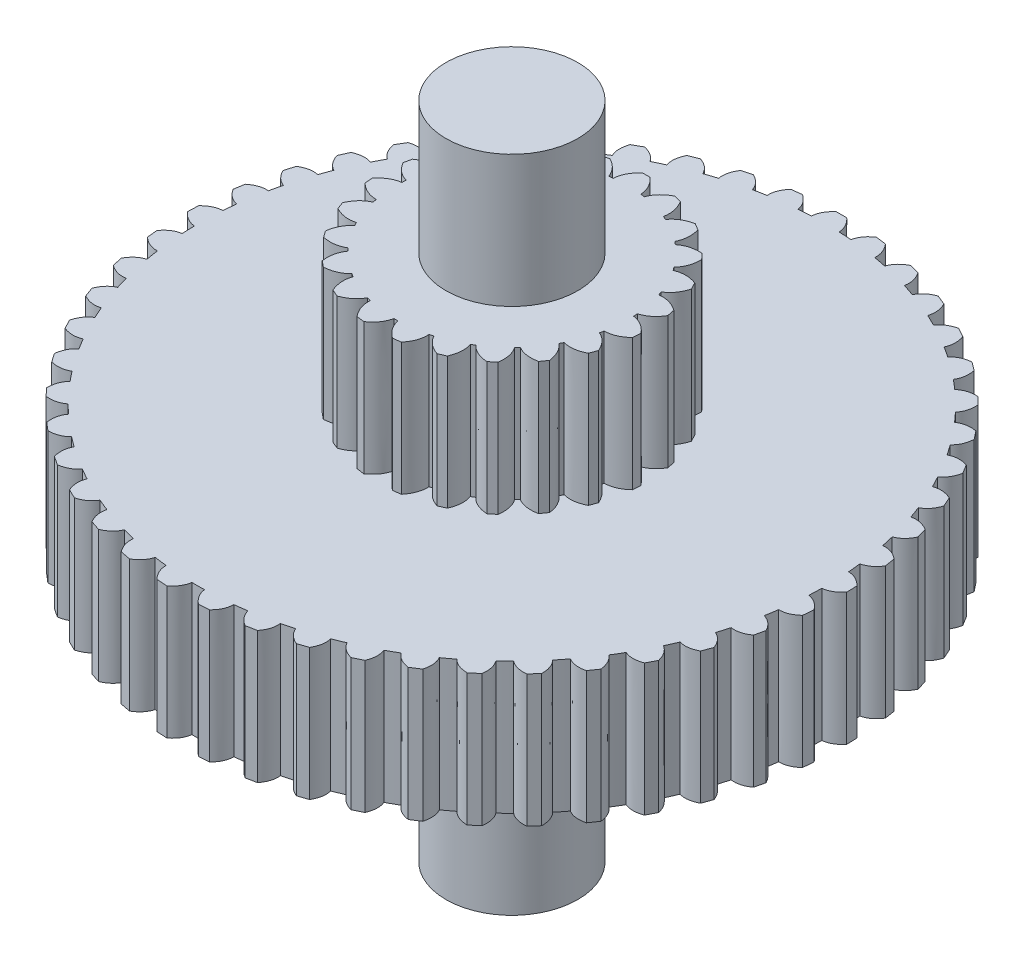
SolidWorks part; units mm, degrees
ref_plane "Front Plane" through (0, 0, 0) normal (0, 0, 1) x (1, 0, 0)
ref_plane "Top Plane" through (0, 0, 0) normal (0, 1, 0) x (1, 0, 0)
ref_plane "Right Plane" through (0, 0, 0) normal (1, 0, 0) x (0, 0, -1)
sketch "Sketch1" plane through (0, 0, 0) normal (0, 1, 0) x (1, 0, 0)
  circle A0 centre (0, 0) radius 2.38
  dimension "D1" = 4.76
extrude "Boss-Extrude1" add sketch "Sketch1" along normal blind 1
sketch "Sketch2" plane through (0, 1, 0) normal (0, 1, 0) x (1, 0, 0)
  line L0 (0, 2.5943) -> (0, 1.7142) construction
  line L1 (0.105, 2.5128) -> (0.105, 2.0785) construction
  line L2 (-0.04, 2.5) -> (0.04, 2.5)
  line L3 (0.28, 2.4846) -> (0.3594, 2.4744)
  line L4 (0.5954, 2.4284) -> (0.6728, 2.4081)
  line L5 (0.9011, 2.3323) -> (0.9752, 2.3023)
  line L6 (1.1919, 2.1979) -> (1.2616, 2.1587)
  line L7 (1.4632, 2.0275) -> (1.5273, 1.9796)
  line L8 (1.7105, 1.8237) -> (1.7679, 1.768)
  line L9 (1.9296, 1.59) -> (1.9795, 1.5275)
  line L10 (2.1171, 1.3302) -> (2.1586, 1.2618)
  line L11 (2.2698, 1.0485) -> (2.3022, 0.9754)
  line L12 (2.3853, 0.7497) -> (2.4081, 0.673)
  line L13 (2.4616, 0.4385) -> (2.4743, 0.3595)
  line L14 (2.4974, 0.1201) -> (2.5, 0.0401)
  line L15 (2.4923, -0.2002) -> (2.4846, -0.2799)
  line L16 (2.4462, -0.5173) -> (2.4284, -0.5953)
  line L17 (2.36, -0.8259) -> (2.3324, -0.901)
  line L18 (2.235, -1.1209) -> (2.198, -1.1918)
  line L19 (2.0733, -1.3975) -> (2.0275, -1.4631)
  line L20 (1.8776, -1.6511) -> (1.8238, -1.7104)
  line L21 (1.651, -1.8777) -> (1.5901, -1.9295)
  line L22 (1.3974, -2.0734) -> (1.3303, -2.117)
  line L23 (1.1207, -2.2351) -> (1.0487, -2.2698)
  line L24 (0.8257, -2.36) -> (0.7498, -2.3852)
  line L25 (0.5172, -2.4463) -> (0.4386, -2.4615)
  line L26 (0.2001, -2.4923) -> (0.1203, -2.4974)
  line L27 (-0.1203, -2.4974) -> (-0.2001, -2.4923)
  line L28 (-0.4386, -2.4615) -> (-0.5172, -2.4463)
  line L29 (-0.7498, -2.3852) -> (-0.8257, -2.36)
  line L30 (-1.0487, -2.2698) -> (-1.1207, -2.2351)
  line L31 (-1.3303, -2.117) -> (-1.3974, -2.0734)
  line L32 (-1.5901, -1.9295) -> (-1.651, -1.8777)
  line L33 (-1.8238, -1.7104) -> (-1.8776, -1.6511)
  line L34 (-2.0275, -1.4631) -> (-2.0733, -1.3975)
  line L35 (-2.198, -1.1918) -> (-2.235, -1.1209)
  line L36 (-2.3324, -0.901) -> (-2.36, -0.8259)
  line L37 (-2.4284, -0.5953) -> (-2.4462, -0.5173)
  line L38 (-2.4846, -0.2799) -> (-2.4923, -0.2002)
  line L39 (-2.5, 0.0401) -> (-2.4974, 0.1201)
  line L40 (-2.4743, 0.3595) -> (-2.4616, 0.4385)
  line L41 (-2.4081, 0.673) -> (-2.3853, 0.7497)
  line L42 (-2.3022, 0.9754) -> (-2.2698, 1.0485)
  line L43 (-2.1586, 1.2618) -> (-2.1171, 1.3302)
  line L44 (-1.9795, 1.5275) -> (-1.9296, 1.59)
  line L45 (-1.7679, 1.768) -> (-1.7105, 1.8237)
  line L46 (-1.5273, 1.9796) -> (-1.4632, 2.0275)
  line L47 (-1.2616, 2.1587) -> (-1.1919, 2.1979)
  line L48 (-0.9752, 2.3023) -> (-0.9011, 2.3323)
  line L49 (-0.6728, 2.4081) -> (-0.5954, 2.4284)
  line L50 (-0.3594, 2.4744) -> (-0.28, 2.4846)
  circle A0 centre (0, 0) radius 2.38 construction
  spline S0 degree 2 poles (0.04, 2.5) (0.1021, 2.4443) (0.105, 2.3743) knots 0 0 0 0.911988 0.911988 0.911988
  spline S1 degree 1 poles (0, 2.38) (0.105, 2.3743) knots 0 0 1 1
  spline S2 degree 1 poles (0, 2.38) (-0.105, 2.3743) knots 0 0 1 1
  spline S3 degree 2 poles (-0.04, 2.5) (-0.1021, 2.4443) (-0.105, 2.3743) knots 0 0 0 0.911988 0.911988 0.911988
  spline S4 degree 2 poles (0.28, 2.4846) (0.2113, 2.4373) (0.1995, 2.3682) knots 0 0 0 0.911988 0.911988 0.911988
  spline S5 degree 1 poles (0.3043, 2.3605) (0.1995, 2.3682) knots 0 0 1 1
  spline S6 degree 1 poles (0.3043, 2.3605) (0.4078, 2.3413) knots 0 0 1 1
  spline S7 degree 2 poles (0.3594, 2.4744) (0.4139, 2.4112) (0.4078, 2.3413) knots 0 0 0 0.911988 0.911988 0.911988
  spline S8 degree 2 poles (0.5954, 2.4284) (0.5212, 2.3903) (0.5007, 2.3232) knots 0 0 0 0.911988 0.911988 0.911988
  spline S9 degree 1 poles (0.6037, 2.3022) (0.5007, 2.3232) knots 0 0 1 1
  spline S10 degree 1 poles (0.6037, 2.3022) (0.7038, 2.27) knots 0 0 1 1
  spline S11 degree 2 poles (0.6728, 2.4081) (0.7188, 2.3385) (0.7038, 2.27) knots 0 0 0 0.911988 0.911988 0.911988
  spline S12 degree 2 poles (0.9011, 2.3323) (0.8226, 2.304) (0.7937, 2.2401) knots 0 0 0 0.911988 0.911988 0.911988
  spline S13 degree 1 poles (0.8931, 2.2061) (0.7937, 2.2401) knots 0 0 1 1
  spline S14 degree 1 poles (0.8931, 2.2061) (0.9883, 2.1613) knots 0 0 1 1
  spline S15 degree 2 poles (0.9752, 2.3023) (1.012, 2.2274) (0.9883, 2.1613) knots 0 0 0 0.911988 0.911988 0.911988
  spline S16 degree 2 poles (1.1919, 2.1979) (1.1105, 2.1799) (1.0736, 2.1203) knots 0 0 0 0.911988 0.911988 0.911988
  spline S17 degree 1 poles (1.1679, 2.0737) (1.0736, 2.1203) knots 0 0 1 1
  spline S18 degree 1 poles (1.1679, 2.0737) (1.2566, 2.0172) knots 0 0 1 1
  spline S19 degree 2 poles (1.2616, 2.1587) (1.2885, 2.0797) (1.2566, 2.0172) knots 0 0 0 0.911988 0.911988 0.911988
  spline S20 degree 2 poles (1.4632, 2.0275) (1.3801, 2.02) (1.3359, 1.9656) knots 0 0 0 0.911988 0.911988 0.911988
  spline S21 degree 1 poles (1.4235, 1.9074) (1.3359, 1.9656) knots 0 0 1 1
  spline S22 degree 1 poles (1.4235, 1.9074) (1.5042, 1.84) knots 0 0 1 1
  spline S23 degree 2 poles (1.5273, 1.9796) (1.5438, 1.8978) (1.5042, 1.84) knots 0 0 0 0.911988 0.911988 0.911988
  spline S24 degree 2 poles (1.7105, 1.8237) (1.6271, 1.8269) (1.5763, 1.7786) knots 0 0 0 0.911988 0.911988 0.911988
  spline S25 degree 1 poles (1.6557, 1.7097) (1.5763, 1.7786) knots 0 0 1 1
  spline S26 degree 1 poles (1.6557, 1.7097) (1.7272, 1.6325) knots 0 0 1 1
  spline S27 degree 2 poles (1.7679, 1.768) (1.7739, 1.6848) (1.7272, 1.6325) knots 0 0 0 0.911988 0.911988 0.911988
  spline S28 degree 2 poles (1.9296, 1.59) (1.8474, 1.6039) (1.7908, 1.5624) knots 0 0 0 0.911988 0.911988 0.911988
  spline S29 degree 1 poles (1.8608, 1.4839) (1.7908, 1.5624) knots 0 0 1 1
  spline S30 degree 1 poles (1.8608, 1.4839) (1.9217, 1.3982) knots 0 0 1 1
  spline S31 degree 2 poles (1.9795, 1.5275) (1.9747, 1.4442) (1.9217, 1.3982) knots 0 0 0 0.911988 0.911988 0.911988
  spline S32 degree 2 poles (2.1171, 1.3302) (2.0373, 1.3545) (1.9759, 1.3206) knots 0 0 0 0.911988 0.911988 0.911988
  spline S33 degree 1 poles (2.0352, 1.2338) (1.9759, 1.3206) knots 0 0 1 1
  spline S34 degree 1 poles (2.0352, 1.2338) (2.0848, 1.141) knots 0 0 1 1
  spline S35 degree 2 poles (2.1586, 1.2618) (2.1432, 1.1798) (2.0848, 1.141) knots 0 0 0 0.911988 0.911988 0.911988
  spline S36 degree 2 poles (2.2698, 1.0485) (2.1938, 1.0828) (2.1285, 1.0571) knots 0 0 0 0.911988 0.911988 0.911988
  spline S37 degree 1 poles (2.1763, 0.9634) (2.1285, 1.0571) knots 0 0 1 1
  spline S38 degree 1 poles (2.1763, 0.9634) (2.2136, 0.865) knots 0 0 1 1
  spline S39 degree 2 poles (2.3022, 0.9754) (2.2765, 0.896) (2.2136, 0.865) knots 0 0 0 0.911988 0.911988 0.911988
  spline S40 degree 2 poles (2.3853, 0.7497) (2.3142, 0.7934) (2.2462, 0.7762) knots 0 0 0 0.911988 0.911988 0.911988
  spline S41 degree 1 poles (2.2816, 0.6772) (2.2462, 0.7762) knots 0 0 1 1
  spline S42 degree 1 poles (2.2816, 0.6772) (2.306, 0.5749) knots 0 0 1 1
  spline S43 degree 2 poles (2.4081, 0.673) (2.3724, 0.5976) (2.306, 0.5749) knots 0 0 0 0.911988 0.911988 0.911988
  spline S44 degree 2 poles (2.4616, 0.4385) (2.3967, 0.4909) (2.3271, 0.4826) knots 0 0 0 0.911988 0.911988 0.911988
  spline S45 degree 1 poles (2.3495, 0.3798) (2.3271, 0.4826) knots 0 0 1 1
  spline S46 degree 1 poles (2.3495, 0.3798) (2.3606, 0.2753) knots 0 0 1 1
  spline S47 degree 2 poles (2.4743, 0.3595) (2.4293, 0.2893) (2.3606, 0.2753) knots 0 0 0 0.911988 0.911988 0.911988
  spline S48 degree 2 poles (2.4974, 0.1201) (2.4398, 0.1804) (2.3697, 0.181) knots 0 0 0 0.911988 0.911988 0.911988
  spline S49 degree 1 poles (2.3788, 0.0763) (2.3697, 0.181) knots 0 0 1 1
  spline S50 degree 1 poles (2.3788, 0.0763) (2.3764, -0.0288) knots 0 0 1 1
  spline S51 degree 2 poles (2.5, 0.0401) (2.4464, -0.0237) (2.3764, -0.0288) knots 0 0 0 0.911988 0.911988 0.911988
  spline S52 degree 2 poles (2.4923, -0.2002) (2.4428, -0.133) (2.3734, -0.1235) knots 0 0 0 0.911988 0.911988 0.911988
  spline S53 degree 1 poles (2.369, -0.2285) (2.3734, -0.1235) knots 0 0 1 1
  spline S54 degree 1 poles (2.369, -0.2285) (2.3532, -0.3325) knots 0 0 1 1
  spline S55 degree 2 poles (2.4846, -0.2799) (2.4232, -0.3364) (2.3532, -0.3325) knots 0 0 0 0.911988 0.911988 0.911988
  spline S56 degree 2 poles (2.4462, -0.5173) (2.4058, -0.4443) (2.3381, -0.426) knots 0 0 0 0.911988 0.911988 0.911988
  spline S57 degree 1 poles (2.3203, -0.5296) (2.3381, -0.426) knots 0 0 1 1
  spline S58 degree 1 poles (2.3203, -0.5296) (2.2914, -0.6307) knots 0 0 1 1
  spline S59 degree 2 poles (2.4284, -0.5953) (2.3603, -0.6435) (2.2914, -0.6307) knots 0 0 0 0.911988 0.911988 0.911988
  spline S60 degree 2 poles (2.36, -0.8259) (2.3292, -0.7483) (2.2644, -0.7214) knots 0 0 0 0.911988 0.911988 0.911988
  spline S61 degree 1 poles (2.2336, -0.822) (2.2644, -0.7214) knots 0 0 1 1
  spline S62 degree 1 poles (2.2336, -0.822) (2.1919, -0.9185) knots 0 0 1 1
  spline S63 degree 2 poles (2.3324, -0.901) (2.2587, -0.94) (2.1919, -0.9185) knots 0 0 0 0.911988 0.911988 0.911988
  spline S64 degree 2 poles (2.235, -1.1209) (2.2144, -1.04) (2.1536, -1.0051) knots 0 0 0 0.911988 0.911988 0.911988
  spline S65 degree 1 poles (2.1101, -1.1008) (2.1536, -1.0051) knots 0 0 1 1
  spline S66 degree 1 poles (2.1101, -1.1008) (2.0564, -1.1913) knots 0 0 1 1
  spline S67 degree 2 poles (2.198, -1.1918) (2.1199, -1.2212) (2.0564, -1.1913) knots 0 0 0 0.911988 0.911988 0.911988
  spline S68 degree 2 poles (2.0733, -1.3975) (2.0632, -1.3147) (2.0074, -1.2722) knots 0 0 0 0.911988 0.911988 0.911988
  spline S69 degree 1 poles (1.952, -1.3616) (2.0074, -1.2722) knots 0 0 1 1
  spline S70 degree 1 poles (1.952, -1.3616) (1.8872, -1.4445) knots 0 0 1 1
  spline S71 degree 2 poles (2.0275, -1.4631) (1.9463, -1.4822) (1.8872, -1.4445) knots 0 0 0 0.911988 0.911988 0.911988
  spline S72 degree 2 poles (1.8776, -1.6511) (1.8782, -1.5677) (1.8282, -1.5185) knots 0 0 0 0.911988 0.911988 0.911988
  spline S73 degree 1 poles (1.7619, -1.6001) (1.8282, -1.5185) knots 0 0 1 1
  spline S74 degree 1 poles (1.7619, -1.6001) (1.687, -1.6739) knots 0 0 1 1
  spline S75 degree 2 poles (1.8238, -1.7104) (1.7408, -1.7189) (1.687, -1.6739) knots 0 0 0 0.911988 0.911988 0.911988
  spline S76 degree 2 poles (1.651, -1.8777) (1.6623, -1.795) (1.619, -1.7398) knots 0 0 0 0.911988 0.911988 0.911988
  spline S77 degree 1 poles (1.5428, -1.8122) (1.619, -1.7398) knots 0 0 1 1
  spline S78 degree 1 poles (1.5428, -1.8122) (1.4591, -1.8759) knots 0 0 1 1
  spline S79 degree 2 poles (1.5901, -1.9295) (1.5067, -1.9274) (1.4591, -1.8759) knots 0 0 0 0.911988 0.911988 0.911988
  spline S80 degree 2 poles (1.3974, -2.0734) (1.4191, -1.9928) (1.3832, -1.9326) knots 0 0 0 0.911988 0.911988 0.911988
  spline S81 degree 1 poles (1.2984, -1.9946) (1.3832, -1.9326) knots 0 0 1 1
  spline S82 degree 1 poles (1.2984, -1.9946) (1.2072, -2.0471) knots 0 0 1 1
  spline S83 degree 2 poles (1.3303, -2.117) (1.2479, -2.1043) (1.2072, -2.0471) knots 0 0 0 0.911988 0.911988 0.911988
  spline S84 degree 2 poles (1.1207, -2.2351) (1.1526, -2.158) (1.1248, -2.0936) knots 0 0 0 0.911988 0.911988 0.911988
  spline S85 degree 1 poles (1.0326, -2.1443) (1.1248, -2.0936) knots 0 0 1 1
  spline S86 degree 1 poles (1.0326, -2.1443) (0.9355, -2.1847) knots 0 0 1 1
  spline S87 degree 2 poles (1.0487, -2.2698) (0.9685, -2.2466) (0.9355, -2.1847) knots 0 0 0 0.911988 0.911988 0.911988
  spline S88 degree 2 poles (0.8257, -2.36) (0.8672, -2.2876) (0.8478, -2.2202) knots 0 0 0 0.911988 0.911988 0.911988
  spline S89 degree 1 poles (0.75, -2.2588) (0.8478, -2.2202) knots 0 0 1 1
  spline S90 degree 1 poles (0.75, -2.2588) (0.6485, -2.2864) knots 0 0 1 1
  spline S91 degree 2 poles (0.7498, -2.3852) (0.6733, -2.352) (0.6485, -2.2864) knots 0 0 0 0.911988 0.911988 0.911988
  spline S92 degree 2 poles (0.5172, -2.4463) (0.5675, -2.3797) (0.5569, -2.3104) knots 0 0 0 0.911988 0.911988 0.911988
  spline S93 degree 1 poles (0.455, -2.3361) (0.5569, -2.3104) knots 0 0 1 1
  spline S94 degree 1 poles (0.455, -2.3361) (0.3508, -2.3505) knots 0 0 1 1
  spline S95 degree 2 poles (0.4386, -2.4615) (0.367, -2.4188) (0.3508, -2.3505) knots 0 0 0 0.911988 0.911988 0.911988
  spline S96 degree 2 poles (0.2001, -2.4923) (0.2585, -2.4328) (0.2569, -2.3626) knots 0 0 0 0.911988 0.911988 0.911988
  spline S97 degree 1 poles (0.1525, -2.3751) (0.2569, -2.3626) knots 0 0 1 1
  spline S98 degree 1 poles (0.1525, -2.3751) (0.0473, -2.3761) knots 0 0 1 1
  spline S99 degree 2 poles (0.1203, -2.4974) (0.0547, -2.4459) (0.0473, -2.3761) knots 0 0 0 0.911988 0.911988 0.911988
  spline S100 degree 2 poles (-0.1203, -2.4974) (-0.0547, -2.4459) (-0.0473, -2.3761) knots 0 0 0 0.911988 0.911988 0.911988
  spline S101 degree 1 poles (-0.1525, -2.3751) (-0.0473, -2.3761) knots 0 0 1 1
  spline S102 degree 1 poles (-0.1525, -2.3751) (-0.2569, -2.3626) knots 0 0 1 1
  spline S103 degree 2 poles (-0.2001, -2.4923) (-0.2585, -2.4328) (-0.2569, -2.3626) knots 0 0 0 0.911988 0.911988 0.911988
  spline S104 degree 2 poles (-0.4386, -2.4615) (-0.367, -2.4188) (-0.3508, -2.3505) knots 0 0 0 0.911988 0.911988 0.911988
  spline S105 degree 1 poles (-0.455, -2.3361) (-0.3508, -2.3505) knots 0 0 1 1
  spline S106 degree 1 poles (-0.455, -2.3361) (-0.5569, -2.3104) knots 0 0 1 1
  spline S107 degree 2 poles (-0.5172, -2.4463) (-0.5675, -2.3797) (-0.5569, -2.3104) knots 0 0 0 0.911988 0.911988 0.911988
  spline S108 degree 2 poles (-0.7498, -2.3852) (-0.6733, -2.352) (-0.6485, -2.2864) knots 0 0 0 0.911988 0.911988 0.911988
  spline S109 degree 1 poles (-0.75, -2.2588) (-0.6485, -2.2864) knots 0 0 1 1
  spline S110 degree 1 poles (-0.75, -2.2588) (-0.8478, -2.2202) knots 0 0 1 1
  spline S111 degree 2 poles (-0.8257, -2.36) (-0.8672, -2.2876) (-0.8478, -2.2202) knots 0 0 0 0.911988 0.911988 0.911988
  spline S112 degree 2 poles (-1.0487, -2.2698) (-0.9685, -2.2466) (-0.9355, -2.1847) knots 0 0 0 0.911988 0.911988 0.911988
  spline S113 degree 1 poles (-1.0326, -2.1443) (-0.9355, -2.1847) knots 0 0 1 1
  spline S114 degree 1 poles (-1.0326, -2.1443) (-1.1248, -2.0936) knots 0 0 1 1
  spline S115 degree 2 poles (-1.1207, -2.2351) (-1.1526, -2.158) (-1.1248, -2.0936) knots 0 0 0 0.911988 0.911988 0.911988
  spline S116 degree 2 poles (-1.3303, -2.117) (-1.2479, -2.1043) (-1.2072, -2.0471) knots 0 0 0 0.911988 0.911988 0.911988
  spline S117 degree 1 poles (-1.2984, -1.9946) (-1.2072, -2.0471) knots 0 0 1 1
  spline S118 degree 1 poles (-1.2984, -1.9946) (-1.3832, -1.9326) knots 0 0 1 1
  spline S119 degree 2 poles (-1.3974, -2.0734) (-1.4191, -1.9928) (-1.3832, -1.9326) knots 0 0 0 0.911988 0.911988 0.911988
  spline S120 degree 2 poles (-1.5901, -1.9295) (-1.5067, -1.9274) (-1.4591, -1.8759) knots 0 0 0 0.911988 0.911988 0.911988
  spline S121 degree 1 poles (-1.5428, -1.8122) (-1.4591, -1.8759) knots 0 0 1 1
  spline S122 degree 1 poles (-1.5428, -1.8122) (-1.619, -1.7398) knots 0 0 1 1
  spline S123 degree 2 poles (-1.651, -1.8777) (-1.6623, -1.795) (-1.619, -1.7398) knots 0 0 0 0.911988 0.911988 0.911988
  spline S124 degree 2 poles (-1.8238, -1.7104) (-1.7408, -1.7189) (-1.687, -1.6739) knots 0 0 0 0.911988 0.911988 0.911988
  spline S125 degree 1 poles (-1.7619, -1.6001) (-1.687, -1.6739) knots 0 0 1 1
  spline S126 degree 1 poles (-1.7619, -1.6001) (-1.8282, -1.5185) knots 0 0 1 1
  spline S127 degree 2 poles (-1.8776, -1.6511) (-1.8782, -1.5677) (-1.8282, -1.5185) knots 0 0 0 0.911988 0.911988 0.911988
  spline S128 degree 2 poles (-2.0275, -1.4631) (-1.9463, -1.4822) (-1.8872, -1.4445) knots 0 0 0 0.911988 0.911988 0.911988
  spline S129 degree 1 poles (-1.952, -1.3616) (-1.8872, -1.4445) knots 0 0 1 1
  spline S130 degree 1 poles (-1.952, -1.3616) (-2.0074, -1.2722) knots 0 0 1 1
  spline S131 degree 2 poles (-2.0733, -1.3975) (-2.0632, -1.3147) (-2.0074, -1.2722) knots 0 0 0 0.911988 0.911988 0.911988
  spline S132 degree 2 poles (-2.198, -1.1918) (-2.1199, -1.2212) (-2.0564, -1.1913) knots 0 0 0 0.911988 0.911988 0.911988
  spline S133 degree 1 poles (-2.1101, -1.1008) (-2.0564, -1.1913) knots 0 0 1 1
  spline S134 degree 1 poles (-2.1101, -1.1008) (-2.1536, -1.0051) knots 0 0 1 1
  spline S135 degree 2 poles (-2.235, -1.1209) (-2.2144, -1.04) (-2.1536, -1.0051) knots 0 0 0 0.911988 0.911988 0.911988
  spline S136 degree 2 poles (-2.3324, -0.901) (-2.2587, -0.94) (-2.1919, -0.9185) knots 0 0 0 0.911988 0.911988 0.911988
  spline S137 degree 1 poles (-2.2336, -0.822) (-2.1919, -0.9185) knots 0 0 1 1
  spline S138 degree 1 poles (-2.2336, -0.822) (-2.2644, -0.7214) knots 0 0 1 1
  spline S139 degree 2 poles (-2.36, -0.8259) (-2.3292, -0.7483) (-2.2644, -0.7214) knots 0 0 0 0.911988 0.911988 0.911988
  spline S140 degree 2 poles (-2.4284, -0.5953) (-2.3603, -0.6435) (-2.2914, -0.6307) knots 0 0 0 0.911988 0.911988 0.911988
  spline S141 degree 1 poles (-2.3203, -0.5296) (-2.2914, -0.6307) knots 0 0 1 1
  spline S142 degree 1 poles (-2.3203, -0.5296) (-2.3381, -0.426) knots 0 0 1 1
  spline S143 degree 2 poles (-2.4462, -0.5173) (-2.4058, -0.4443) (-2.3381, -0.426) knots 0 0 0 0.911988 0.911988 0.911988
  spline S144 degree 2 poles (-2.4846, -0.2799) (-2.4232, -0.3364) (-2.3532, -0.3325) knots 0 0 0 0.911988 0.911988 0.911988
  spline S145 degree 1 poles (-2.369, -0.2285) (-2.3532, -0.3325) knots 0 0 1 1
  spline S146 degree 1 poles (-2.369, -0.2285) (-2.3734, -0.1235) knots 0 0 1 1
  spline S147 degree 2 poles (-2.4923, -0.2002) (-2.4428, -0.133) (-2.3734, -0.1235) knots 0 0 0 0.911988 0.911988 0.911988
  spline S148 degree 2 poles (-2.5, 0.0401) (-2.4464, -0.0237) (-2.3764, -0.0288) knots 0 0 0 0.911988 0.911988 0.911988
  spline S149 degree 1 poles (-2.3788, 0.0763) (-2.3764, -0.0288) knots 0 0 1 1
  spline S150 degree 1 poles (-2.3788, 0.0763) (-2.3697, 0.181) knots 0 0 1 1
  spline S151 degree 2 poles (-2.4974, 0.1201) (-2.4398, 0.1804) (-2.3697, 0.181) knots 0 0 0 0.911988 0.911988 0.911988
  spline S152 degree 2 poles (-2.4743, 0.3595) (-2.4293, 0.2893) (-2.3606, 0.2753) knots 0 0 0 0.911988 0.911988 0.911988
  spline S153 degree 1 poles (-2.3495, 0.3798) (-2.3606, 0.2753) knots 0 0 1 1
  spline S154 degree 1 poles (-2.3495, 0.3798) (-2.3271, 0.4826) knots 0 0 1 1
  spline S155 degree 2 poles (-2.4616, 0.4385) (-2.3967, 0.4909) (-2.3271, 0.4826) knots 0 0 0 0.911988 0.911988 0.911988
  spline S156 degree 2 poles (-2.4081, 0.673) (-2.3724, 0.5976) (-2.306, 0.5749) knots 0 0 0 0.911988 0.911988 0.911988
  spline S157 degree 1 poles (-2.2816, 0.6772) (-2.306, 0.5749) knots 0 0 1 1
  spline S158 degree 1 poles (-2.2816, 0.6772) (-2.2462, 0.7762) knots 0 0 1 1
  spline S159 degree 2 poles (-2.3853, 0.7497) (-2.3142, 0.7934) (-2.2462, 0.7762) knots 0 0 0 0.911988 0.911988 0.911988
  spline S160 degree 2 poles (-2.3022, 0.9754) (-2.2765, 0.896) (-2.2136, 0.865) knots 0 0 0 0.911988 0.911988 0.911988
  spline S161 degree 1 poles (-2.1763, 0.9634) (-2.2136, 0.865) knots 0 0 1 1
  spline S162 degree 1 poles (-2.1763, 0.9634) (-2.1285, 1.0571) knots 0 0 1 1
  spline S163 degree 2 poles (-2.2698, 1.0485) (-2.1938, 1.0828) (-2.1285, 1.0571) knots 0 0 0 0.911988 0.911988 0.911988
  spline S164 degree 2 poles (-2.1586, 1.2618) (-2.1432, 1.1798) (-2.0848, 1.141) knots 0 0 0 0.911988 0.911988 0.911988
  spline S165 degree 1 poles (-2.0352, 1.2338) (-2.0848, 1.141) knots 0 0 1 1
  spline S166 degree 1 poles (-2.0352, 1.2338) (-1.9759, 1.3206) knots 0 0 1 1
  spline S167 degree 2 poles (-2.1171, 1.3302) (-2.0373, 1.3545) (-1.9759, 1.3206) knots 0 0 0 0.911988 0.911988 0.911988
  spline S168 degree 2 poles (-1.9795, 1.5275) (-1.9747, 1.4442) (-1.9217, 1.3982) knots 0 0 0 0.911988 0.911988 0.911988
  spline S169 degree 1 poles (-1.8608, 1.4839) (-1.9217, 1.3982) knots 0 0 1 1
  spline S170 degree 1 poles (-1.8608, 1.4839) (-1.7908, 1.5624) knots 0 0 1 1
  spline S171 degree 2 poles (-1.9296, 1.59) (-1.8474, 1.6039) (-1.7908, 1.5624) knots 0 0 0 0.911988 0.911988 0.911988
  spline S172 degree 2 poles (-1.7679, 1.768) (-1.7739, 1.6848) (-1.7272, 1.6325) knots 0 0 0 0.911988 0.911988 0.911988
  spline S173 degree 1 poles (-1.6557, 1.7097) (-1.7272, 1.6325) knots 0 0 1 1
  spline S174 degree 1 poles (-1.6557, 1.7097) (-1.5763, 1.7786) knots 0 0 1 1
  spline S175 degree 2 poles (-1.7105, 1.8237) (-1.6271, 1.8269) (-1.5763, 1.7786) knots 0 0 0 0.911988 0.911988 0.911988
  spline S176 degree 2 poles (-1.5273, 1.9796) (-1.5438, 1.8978) (-1.5042, 1.84) knots 0 0 0 0.911988 0.911988 0.911988
  spline S177 degree 1 poles (-1.4235, 1.9074) (-1.5042, 1.84) knots 0 0 1 1
  spline S178 degree 1 poles (-1.4235, 1.9074) (-1.3359, 1.9656) knots 0 0 1 1
  spline S179 degree 2 poles (-1.4632, 2.0275) (-1.3801, 2.02) (-1.3359, 1.9656) knots 0 0 0 0.911988 0.911988 0.911988
  spline S180 degree 2 poles (-1.2616, 2.1587) (-1.2885, 2.0797) (-1.2566, 2.0172) knots 0 0 0 0.911988 0.911988 0.911988
  spline S181 degree 1 poles (-1.1679, 2.0737) (-1.2566, 2.0172) knots 0 0 1 1
  spline S182 degree 1 poles (-1.1679, 2.0737) (-1.0736, 2.1203) knots 0 0 1 1
  spline S183 degree 2 poles (-1.1919, 2.1979) (-1.1105, 2.1799) (-1.0736, 2.1203) knots 0 0 0 0.911988 0.911988 0.911988
  spline S184 degree 2 poles (-0.9752, 2.3023) (-1.012, 2.2274) (-0.9883, 2.1613) knots 0 0 0 0.911988 0.911988 0.911988
  spline S185 degree 1 poles (-0.8931, 2.2061) (-0.9883, 2.1613) knots 0 0 1 1
  spline S186 degree 1 poles (-0.8931, 2.2061) (-0.7937, 2.2401) knots 0 0 1 1
  spline S187 degree 2 poles (-0.9011, 2.3323) (-0.8226, 2.304) (-0.7937, 2.2401) knots 0 0 0 0.911988 0.911988 0.911988
  spline S188 degree 2 poles (-0.6728, 2.4081) (-0.7188, 2.3385) (-0.7038, 2.27) knots 0 0 0 0.911988 0.911988 0.911988
  spline S189 degree 1 poles (-0.6037, 2.3022) (-0.7038, 2.27) knots 0 0 1 1
  spline S190 degree 1 poles (-0.6037, 2.3022) (-0.5007, 2.3232) knots 0 0 1 1
  spline S191 degree 2 poles (-0.5954, 2.4284) (-0.5212, 2.3903) (-0.5007, 2.3232) knots 0 0 0 0.911988 0.911988 0.911988
  spline S192 degree 2 poles (-0.3594, 2.4744) (-0.4139, 2.4112) (-0.4078, 2.3413) knots 0 0 0 0.911988 0.911988 0.911988
  spline S193 degree 1 poles (-0.3043, 2.3605) (-0.4078, 2.3413) knots 0 0 1 1
  spline S194 degree 1 poles (-0.3043, 2.3605) (-0.1995, 2.3682) knots 0 0 1 1
  spline S195 degree 2 poles (-0.28, 2.4846) (-0.2113, 2.4373) (-0.1995, 2.3682) knots 0 0 0 0.911988 0.911988 0.911988
  point P13 (0, 2.5)
  dimension "D1" = 0.105
  dimension "D2" = 0.04
  dimension "D3" = 2.5
extrude "Boss-Extrude2" add sketch "Sketch2" against normal blind 1
sketch "Sketch3" plane through (0, 1, 0) normal (0, 1, 0) x (1, 0, 0)
  circle A0 centre (0, 0) radius 0.88
  dimension "D1" = 1.76
extrude "Boss-Extrude3" add sketch "Sketch3" along normal blind 1
sketch "Sketch4" plane through (0, 2, 0) normal (0, 1, 0) x (1, 0, 0)
  line L0 (0, 1.0523) -> (0, 0.6388) construction
  line L1 (0.105, 0.9663) -> (0.105, 0.705) construction
  line L2 (-0.03, 1.0197) -> (0.03, 1.0197)
  line L3 (0.2462, 0.9899) -> (0.304, 0.9738)
  line L4 (0.5042, 0.8868) -> (0.5554, 0.8556)
  line L5 (0.7247, 0.7179) -> (0.7657, 0.674)
  line L6 (0.8915, 0.4957) -> (0.9191, 0.4425)
  line L7 (0.9922, 0.2368) -> (1.0044, 0.1781)
  line L8 (1.0193, -0.0397) -> (1.0152, -0.0995)
  line L9 (0.9708, -0.3132) -> (0.9507, -0.3697)
  line L10 (0.8503, -0.5635) -> (0.8157, -0.6125)
  line L11 (0.6668, -0.772) -> (0.6202, -0.8099)
  line L12 (0.4338, -0.9233) -> (0.3787, -0.9472)
  line L13 (0.1686, -1.0061) -> (0.1091, -1.0143)
  line L14 (-0.1091, -1.0143) -> (-0.1686, -1.0061)
  line L15 (-0.3787, -0.9472) -> (-0.4338, -0.9233)
  line L16 (-0.6202, -0.8099) -> (-0.6668, -0.772)
  line L17 (-0.8157, -0.6125) -> (-0.8503, -0.5635)
  line L18 (-0.9507, -0.3697) -> (-0.9708, -0.3132)
  line L19 (-1.0152, -0.0995) -> (-1.0193, -0.0397)
  line L20 (-1.0044, 0.1781) -> (-0.9922, 0.2368)
  line L21 (-0.9191, 0.4425) -> (-0.8915, 0.4957)
  line L22 (-0.7657, 0.674) -> (-0.7247, 0.7179)
  line L23 (-0.5554, 0.8556) -> (-0.5042, 0.8868)
  line L24 (-0.304, 0.9738) -> (-0.2462, 0.9899)
  circle A0 centre (0, 0) radius 0.88 construction
  spline S0 degree 2 poles (0.03, 1.0197) (0.1014, 0.9525) (0.105, 0.8694) knots 0 0 0 0.904085 0.904085 0.904085
  spline S1 degree 1 poles (0, 0.88) (0.105, 0.8694) knots 0 0 1 1
  spline S2 degree 1 poles (0, 0.88) (-0.105, 0.8694) knots 0 0 1 1
  spline S3 degree 2 poles (-0.03, 1.0197) (-0.1014, 0.9525) (-0.105, 0.8694) knots 0 0 0 0.904085 0.904085 0.904085
  spline S4 degree 2 poles (0.2462, 0.9899) (0.1593, 0.9446) (0.1335, 0.8655) knots 0 0 0 0.904085 0.904085 0.904085
  spline S5 degree 2 poles (0.304, 0.9738) (0.3546, 0.8898) (0.3357, 0.8088) knots 0 0 0 0.904085 0.904085 0.904085
  spline S6 degree 1 poles (0.2374, 0.8474) (0.3357, 0.8088) knots 0 0 1 1
  spline S7 degree 1 poles (0.2374, 0.8474) (0.1335, 0.8655) knots 0 0 1 1
  spline S8 degree 2 poles (0.5042, 0.8868) (0.4083, 0.8665) (0.362, 0.7974) knots 0 0 0 0.904085 0.904085 0.904085
  spline S9 degree 2 poles (0.5554, 0.8556) (0.5816, 0.7612) (0.5414, 0.6883) knots 0 0 0 0.904085 0.904085 0.904085
  spline S10 degree 1 poles (0.4572, 0.7519) (0.5414, 0.6883) knots 0 0 1 1
  spline S11 degree 1 poles (0.4572, 0.7519) (0.362, 0.7974) knots 0 0 1 1
  spline S12 degree 2 poles (0.7247, 0.7179) (0.6269, 0.7243) (0.5637, 0.6701) knots 0 0 0 0.904085 0.904085 0.904085
  spline S13 degree 2 poles (0.7657, 0.674) (0.7653, 0.576) (0.707, 0.5167) knots 0 0 0 0.904085 0.904085 0.904085
  spline S14 degree 1 poles (0.6431, 0.6006) (0.707, 0.5167) knots 0 0 1 1
  spline S15 degree 1 poles (0.6431, 0.6006) (0.5637, 0.6701) knots 0 0 1 1
  spline S16 degree 2 poles (0.8915, 0.4957) (0.7991, 0.5283) (0.7236, 0.4932) knots 0 0 0 0.904085 0.904085 0.904085
  spline S17 degree 2 poles (0.9191, 0.4425) (0.8924, 0.3482) (0.8202, 0.3067) knots 0 0 0 0.904085 0.904085 0.904085
  spline S18 degree 1 poles (0.7813, 0.4049) (0.8202, 0.3067) knots 0 0 1 1
  spline S19 degree 1 poles (0.7813, 0.4049) (0.7236, 0.4932) knots 0 0 1 1
  spline S20 degree 2 poles (0.9922, 0.2368) (0.912, 0.2931) (0.8298, 0.2797) knots 0 0 0 0.904085 0.904085 0.904085
  spline S21 degree 2 poles (1.0044, 0.1781) (0.9532, 0.0945) (0.8726, 0.0741) knots 0 0 0 0.904085 0.904085 0.904085
  spline S22 degree 1 poles (0.8616, 0.179) (0.8726, 0.0741) knots 0 0 1 1
  spline S23 degree 1 poles (0.8616, 0.179) (0.8298, 0.2797) knots 0 0 1 1
  spline S24 degree 2 poles (1.0193, -0.0397) (0.9572, 0.0362) (0.8745, 0.0454) knots 0 0 0 0.904085 0.904085 0.904085
  spline S25 degree 2 poles (1.0152, -0.0995) (0.9434, -0.1662) (0.8602, -0.1641) knots 0 0 0 0.904085 0.904085 0.904085
  spline S26 degree 1 poles (0.8779, -0.0601) (0.8602, -0.1641) knots 0 0 1 1
  spline S27 degree 1 poles (0.8779, -0.0601) (0.8745, 0.0454) knots 0 0 1 1
  spline S28 degree 2 poles (0.9708, -0.3132) (0.9315, -0.2234) (0.8544, -0.1922) knots 0 0 0 0.904085 0.904085 0.904085
  spline S29 degree 2 poles (0.9507, -0.3697) (0.8636, -0.4145) (0.784, -0.3901) knots 0 0 0 0.904085 0.904085 0.904085
  spline S30 degree 1 poles (0.8292, -0.2947) (0.784, -0.3901) knots 0 0 1 1
  spline S31 degree 1 poles (0.8292, -0.2947) (0.8544, -0.1922) knots 0 0 1 1
  spline S32 degree 2 poles (0.8503, -0.5635) (0.8367, -0.4665) (0.7708, -0.4156) knots 0 0 0 0.904085 0.904085 0.904085
  spline S33 degree 2 poles (0.8157, -0.6125) (0.7197, -0.6321) (0.6497, -0.5871) knots 0 0 0 0.904085 0.904085 0.904085
  spline S34 degree 1 poles (0.7189, -0.5075) (0.6497, -0.5871) knots 0 0 1 1
  spline S35 degree 1 poles (0.7189, -0.5075) (0.7708, -0.4156) knots 0 0 1 1
  spline S36 degree 2 poles (0.6668, -0.772) (0.6798, -0.6749) (0.6301, -0.6081) knots 0 0 0 0.904085 0.904085 0.904085
  spline S37 degree 2 poles (0.6202, -0.8099) (0.5225, -0.8029) (0.4672, -0.7407) knots 0 0 0 0.904085 0.904085 0.904085
  spline S38 degree 1 poles (0.5554, -0.6826) (0.4672, -0.7407) knots 0 0 1 1
  spline S39 degree 1 poles (0.5554, -0.6826) (0.6301, -0.6081) knots 0 0 1 1
  spline S40 degree 2 poles (0.4338, -0.9233) (0.4725, -0.8333) (0.4427, -0.7556) knots 0 0 0 0.904085 0.904085 0.904085
  spline S41 degree 2 poles (0.3787, -0.9472) (0.2865, -0.9141) (0.2501, -0.8392) knots 0 0 0 0.904085 0.904085 0.904085
  spline S42 degree 1 poles (0.3506, -0.8071) (0.2501, -0.8392) knots 0 0 1 1
  spline S43 degree 1 poles (0.3506, -0.8071) (0.4427, -0.7556) knots 0 0 1 1
  spline S44 degree 2 poles (0.1686, -1.0061) (0.2302, -0.9298) (0.2224, -0.847) knots 0 0 0 0.904085 0.904085 0.904085
  spline S45 degree 2 poles (0.1091, -1.0143) (0.0292, -0.9575) (0.0144, -0.8756) knots 0 0 0 0.904085 0.904085 0.904085
  spline S46 degree 1 poles (0.1198, -0.8718) (0.0144, -0.8756) knots 0 0 1 1
  spline S47 degree 1 poles (0.1198, -0.8718) (0.2224, -0.847) knots 0 0 1 1
  spline S48 degree 2 poles (-0.1091, -1.0143) (-0.0292, -0.9575) (-0.0144, -0.8756) knots 0 0 0 0.904085 0.904085 0.904085
  spline S49 degree 2 poles (-0.1686, -1.0061) (-0.2302, -0.9298) (-0.2224, -0.847) knots 0 0 0 0.904085 0.904085 0.904085
  spline S50 degree 1 poles (-0.1198, -0.8718) (-0.2224, -0.847) knots 0 0 1 1
  spline S51 degree 1 poles (-0.1198, -0.8718) (-0.0144, -0.8756) knots 0 0 1 1
  spline S52 degree 2 poles (-0.3787, -0.9472) (-0.2865, -0.9141) (-0.2501, -0.8392) knots 0 0 0 0.904085 0.904085 0.904085
  spline S53 degree 2 poles (-0.4338, -0.9233) (-0.4725, -0.8333) (-0.4427, -0.7556) knots 0 0 0 0.904085 0.904085 0.904085
  spline S54 degree 1 poles (-0.3506, -0.8071) (-0.4427, -0.7556) knots 0 0 1 1
  spline S55 degree 1 poles (-0.3506, -0.8071) (-0.2501, -0.8392) knots 0 0 1 1
  spline S56 degree 2 poles (-0.6202, -0.8099) (-0.5225, -0.8029) (-0.4672, -0.7407) knots 0 0 0 0.904085 0.904085 0.904085
  spline S57 degree 2 poles (-0.6668, -0.772) (-0.6798, -0.6749) (-0.6301, -0.6081) knots 0 0 0 0.904085 0.904085 0.904085
  spline S58 degree 1 poles (-0.5554, -0.6826) (-0.6301, -0.6081) knots 0 0 1 1
  spline S59 degree 1 poles (-0.5554, -0.6826) (-0.4672, -0.7407) knots 0 0 1 1
  spline S60 degree 2 poles (-0.8157, -0.6125) (-0.7197, -0.6321) (-0.6497, -0.5871) knots 0 0 0 0.904085 0.904085 0.904085
  spline S61 degree 2 poles (-0.8503, -0.5635) (-0.8367, -0.4665) (-0.7708, -0.4156) knots 0 0 0 0.904085 0.904085 0.904085
  spline S62 degree 1 poles (-0.7189, -0.5075) (-0.7708, -0.4156) knots 0 0 1 1
  spline S63 degree 1 poles (-0.7189, -0.5075) (-0.6497, -0.5871) knots 0 0 1 1
  spline S64 degree 2 poles (-0.9507, -0.3697) (-0.8636, -0.4145) (-0.784, -0.3901) knots 0 0 0 0.904085 0.904085 0.904085
  spline S65 degree 2 poles (-0.9708, -0.3132) (-0.9315, -0.2234) (-0.8544, -0.1922) knots 0 0 0 0.904085 0.904085 0.904085
  spline S66 degree 1 poles (-0.8292, -0.2947) (-0.8544, -0.1922) knots 0 0 1 1
  spline S67 degree 1 poles (-0.8292, -0.2947) (-0.784, -0.3901) knots 0 0 1 1
  spline S68 degree 2 poles (-1.0152, -0.0995) (-0.9434, -0.1662) (-0.8602, -0.1641) knots 0 0 0 0.904085 0.904085 0.904085
  spline S69 degree 2 poles (-1.0193, -0.0397) (-0.9572, 0.0362) (-0.8745, 0.0454) knots 0 0 0 0.904085 0.904085 0.904085
  spline S70 degree 1 poles (-0.8779, -0.0601) (-0.8745, 0.0454) knots 0 0 1 1
  spline S71 degree 1 poles (-0.8779, -0.0601) (-0.8602, -0.1641) knots 0 0 1 1
  spline S72 degree 2 poles (-1.0044, 0.1781) (-0.9532, 0.0945) (-0.8726, 0.0741) knots 0 0 0 0.904085 0.904085 0.904085
  spline S73 degree 2 poles (-0.9922, 0.2368) (-0.912, 0.2931) (-0.8298, 0.2797) knots 0 0 0 0.904085 0.904085 0.904085
  spline S74 degree 1 poles (-0.8616, 0.179) (-0.8298, 0.2797) knots 0 0 1 1
  spline S75 degree 1 poles (-0.8616, 0.179) (-0.8726, 0.0741) knots 0 0 1 1
  spline S76 degree 2 poles (-0.9191, 0.4425) (-0.8924, 0.3482) (-0.8202, 0.3067) knots 0 0 0 0.904085 0.904085 0.904085
  spline S77 degree 2 poles (-0.8915, 0.4957) (-0.7991, 0.5283) (-0.7236, 0.4932) knots 0 0 0 0.904085 0.904085 0.904085
  spline S78 degree 1 poles (-0.7813, 0.4049) (-0.7236, 0.4932) knots 0 0 1 1
  spline S79 degree 1 poles (-0.7813, 0.4049) (-0.8202, 0.3067) knots 0 0 1 1
  spline S80 degree 2 poles (-0.7657, 0.674) (-0.7653, 0.576) (-0.707, 0.5167) knots 0 0 0 0.904085 0.904085 0.904085
  spline S81 degree 2 poles (-0.7247, 0.7179) (-0.6269, 0.7243) (-0.5637, 0.6701) knots 0 0 0 0.904085 0.904085 0.904085
  spline S82 degree 1 poles (-0.6431, 0.6006) (-0.5637, 0.6701) knots 0 0 1 1
  spline S83 degree 1 poles (-0.6431, 0.6006) (-0.707, 0.5167) knots 0 0 1 1
  spline S84 degree 2 poles (-0.5554, 0.8556) (-0.5816, 0.7612) (-0.5414, 0.6883) knots 0 0 0 0.904085 0.904085 0.904085
  spline S85 degree 2 poles (-0.5042, 0.8868) (-0.4083, 0.8665) (-0.362, 0.7974) knots 0 0 0 0.904085 0.904085 0.904085
  spline S86 degree 1 poles (-0.4572, 0.7519) (-0.362, 0.7974) knots 0 0 1 1
  spline S87 degree 1 poles (-0.4572, 0.7519) (-0.5414, 0.6883) knots 0 0 1 1
  spline S88 degree 2 poles (-0.304, 0.9738) (-0.3546, 0.8898) (-0.3357, 0.8088) knots 0 0 0 0.904085 0.904085 0.904085
  spline S89 degree 2 poles (-0.2462, 0.9899) (-0.1593, 0.9446) (-0.1335, 0.8655) knots 0 0 0 0.904085 0.904085 0.904085
  spline S90 degree 1 poles (-0.2374, 0.8474) (-0.1335, 0.8655) knots 0 0 1 1
  spline S91 degree 1 poles (-0.2374, 0.8474) (-0.3357, 0.8088) knots 0 0 1 1
  point P11 (0, 1.0197)
  dimension "D1" = 0.105
  dimension "D2" = 0.03
extrude "Boss-Extrude4" add sketch "Sketch4" against normal blind 1
sketch "Sketch5" plane through (0, 2, 0) normal (0, 1, 0) x (1, 0, 0)
  circle A0 centre (0, 0) radius 0.5
  dimension "D1" = 1
extrude "Boss-Extrude5" add sketch "Sketch5" along normal blind 1
sketch "Sketch6" plane through (0, 0, 0) normal (0, -1, 0) x (1, 0, 0)
  circle A0 centre (0, 0) radius 0.5
  dimension "D1" = 1
extrude "Boss-Extrude7" add sketch "Sketch6" along normal blind 2
